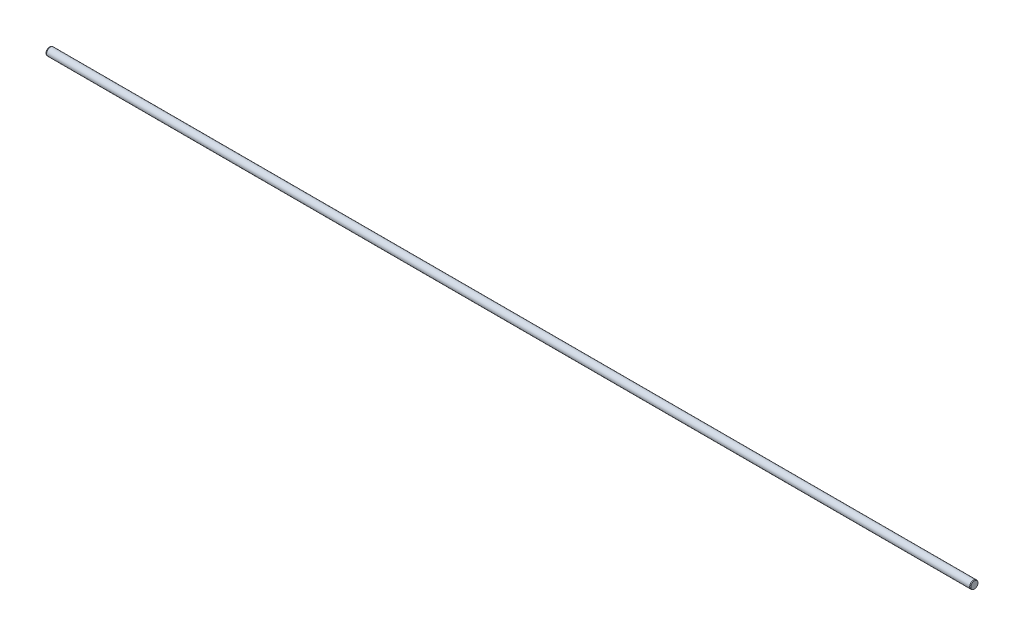
SolidWorks part; units mm, degrees
ref_plane "Front Plane" through (0, 0, 0) normal (0, 0, 1) x (1, 0, 0)
ref_plane "Top Plane" through (0, 0, 0) normal (0, 1, 0) x (1, 0, 0)
ref_plane "Right Plane" through (0, 0, 0) normal (1, 0, 0) x (0, 0, -1)
sketch "Sketch1" plane through (0, 0, 0) normal (1, 0, 0) x (0, 0, -1)
  circle A0 centre (0, 0) radius 5 construction
  dimension "Diameter" = 10
sketch "Sketch2" plane through (0, 0, 0) normal (0, 0, 1) x (1, 0, 0)
  line L0 (0, 0) -> (600, 0) construction
  line L1 (0, 0) -> (-600, 0) construction
  line L2 (600, 0) -> (600, 5) construction
  line L3 (600, 0) -> (600, -5) construction
  line L4 (600, 5) -> (0, 5) construction
  line L7 (0, 5) -> (-600, 5) construction
  line L8 (-600, 5) -> (-600, 0) construction
  point P5 (-549.2, 0)
  point P8 (549.2, 0)
  dimension "Length" = 1200
  dimension "D1" = 50.8
  dimension "D2" = 50.8
sketch "Sketch4" plane through (0, 0, 0) normal (1, 0, 0) x (0, 0, -1)
  circle A0 centre (0, 0) radius 5 construction
  circle A1 centre (0, 0) radius 5
extrude "Boss-Extrude1" add sketch "Sketch4" along normal up to vertex (600 mm away) and the other way up to vertex (600 mm away) up to point (600, 0, 0) other way up to point (-600, 0, 0)
chamfer "Chamfer1" distance 0.3 angle 75 2 edges at (-600, 0, -5) (600, 0, -5)
equation "\"D1@Chamfer1\"=\"Diameter@Sketch1\" * .03"
equation "\"D2@Sketch2\" = \"D1@Sketch2\""
